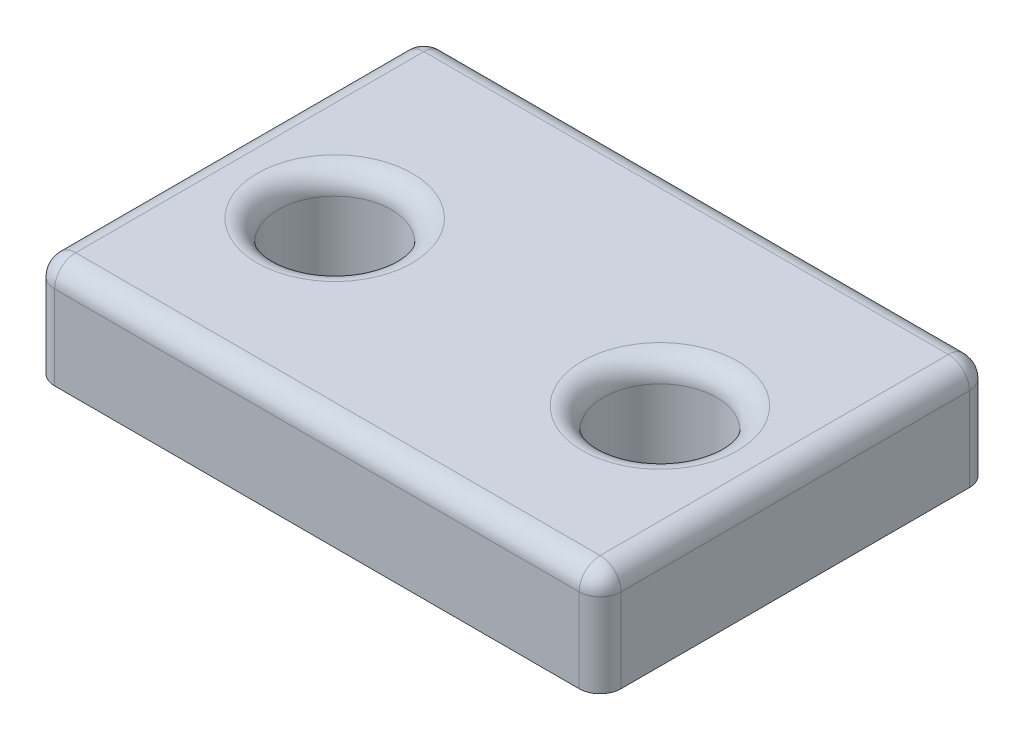
SolidWorks part; units mm, degrees
ref_plane "前视基准面" through (0, 0, 0) normal (0, 0, 1) x (1, 0, 0)
ref_plane "上视基准面" through (0, 0, 0) normal (0, 1, 0) x (1, 0, 0)
ref_plane "右视基准面" through (0, 0, 0) normal (1, 0, 0) x (0, 0, -1)
other "Configuration Table"
sketch "草图1" plane through (0, 0, 0) normal (0, 1, 0) x (1, 0, 0)
  line L1 (0, 0) -> (27, 0)
  line L2 (0, 0) -> (0, -18.6)
  line L3 (0, -18.6) -> (27, -18.6)
  line L4 (27, 0) -> (27, -18.6)
  circle A0 centre (5.75, -10) radius 2.7
  circle A1 centre (21.25, -10) radius 2.7
  dimension "D4" = 5.4
  dimension "D5" = 5.4
  dimension "D1" = 27
  dimension "D2" = 18.6
  dimension "D3" = 15.5
  dimension "D6" = 5.75
  dimension "D7" = 10
extrude "凸台-拉伸1" add sketch "草图1" along normal blind 5
fillet "圆角2" radius 1 4 edges at (0, 2.5, 0) (27, 2.5, 0) (0, 2.5, 18.6) (27, 2.5, 18.6)
fillet "圆角3" radius 1 10 edges at (21.25, 5, 12.7) (26.7071, 5, 0.2929) (27, 5, 9.3) (26.7071, 5, 18.3071) (13.5, 5, 18.6) (0.2929, 5, 18.3071) (0, 5, 9.3) (0.2929, 5, 0.2929) (13.5, 5, 0) (5.75, 5, 12.7)
equation "\"D6@草图1\"=27/2 - 15.5/2"
